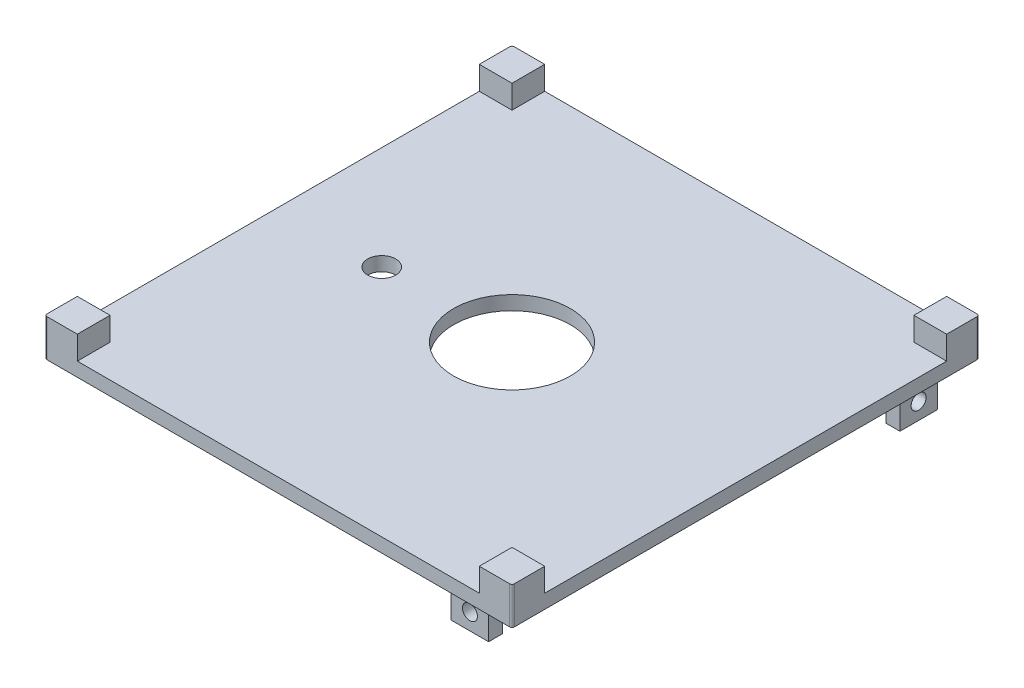
SolidWorks part; units mm, degrees
material "6061-T6 (SS)"
ref_plane "Front Plane" through (0, 0, 0) normal (0, 0, 1) x (1, 0, 0)
ref_plane "Top Plane" through (0, 0, 0) normal (0, 1, 0) x (1, 0, 0)
ref_plane "Right Plane" through (0, 0, 0) normal (1, 0, 0) x (0, 0, -1)
sketch "Sketch1" plane through (0, 0, 0) normal (0, 1, 0) x (1, 0, 0)
  line L0 (50, -50) -> (-50, -50) construction
  line L1 (50, -50) -> (50, 50) construction
  line L2 (50, 50) -> (-50, 50) construction
  line L3 (-50, -50) -> (-50, 50) construction
  line L4 (50, -50) -> (-50, 50) construction
  line L5 (50, 50) -> (-50, -50) construction
  line L6 (-50, 50) -> (-43, 50) construction
  line L7 (-50, 50) -> (-50, 43) construction
  line L8 (-50, 43) -> (-43, 43) construction
  line L9 (-43, 50) -> (-43, 43) construction
  line L10 (-50, -50) -> (-43, -50) construction
  line L11 (-50, -50) -> (-50, -43) construction
  line L12 (-50, -43) -> (-43, -43) construction
  line L13 (-43, -50) -> (-43, -43) construction
  line L14 (50, -50) -> (43, -50) construction
  line L15 (50, -50) -> (50, -43) construction
  line L16 (50, -43) -> (43, -43) construction
  line L17 (43, -50) -> (43, -43) construction
  line L18 (50, 50) -> (43, 50) construction
  line L19 (50, 50) -> (50, 43) construction
  line L20 (50, 43) -> (43, 43) construction
  line L21 (43, 50) -> (43, 43) construction
  line L22 (-32.625, 45.061) -> (33.923, 45.061) construction
  line L23 (-32.625, 45.061) -> (-32.625, 35.082) construction
  line L24 (-32.625, 35.082) -> (33.923, 35.082) construction
  line L25 (33.923, 45.061) -> (33.923, 35.082) construction
  line L26 (-50, 50) -> (-35, 50)
  line L27 (-50, 50) -> (-50, 48)
  line L28 (-50, 48) -> (-35, 48)
  line L29 (-35, 50) -> (-35, 48)
  line L30 (-50, 50) -> (-48, 50)
  line L31 (-50, 50) -> (-50, 35)
  line L32 (-50, 35) -> (-48, 35)
  line L33 (-48, 50) -> (-48, 35)
  line L34 (50, 50) -> (35, 50)
  line L35 (50, 50) -> (50, 48)
  line L36 (50, 48) -> (35, 48)
  line L37 (35, 50) -> (35, 48)
  line L38 (50, 50) -> (48, 50)
  line L39 (50, 50) -> (50, 35)
  line L40 (50, 35) -> (48, 35)
  line L41 (48, 50) -> (48, 35)
  line L42 (50, -50) -> (48, -50)
  line L43 (50, -50) -> (50, -35)
  line L44 (50, -35) -> (48, -35)
  line L45 (48, -50) -> (48, -35)
  line L46 (50, -50) -> (35, -50)
  line L47 (50, -50) -> (50, -48)
  line L48 (50, -48) -> (35, -48)
  line L49 (35, -50) -> (35, -48)
  line L50 (-50, -50) -> (-35, -50)
  line L51 (-50, -50) -> (-50, -48)
  line L52 (-50, -48) -> (-35, -48)
  line L53 (-35, -50) -> (-35, -48)
  line L54 (-50, -50) -> (-48, -50)
  line L55 (-50, -50) -> (-50, -35)
  line L56 (-50, -35) -> (-48, -35)
  line L57 (-48, -50) -> (-48, -35)
  circle A0 centre (-36.2, 42.85) radius 1.6
  circle A1 centre (37.5, 42.85) radius 1.6
  circle A2 centre (40, -42.85) radius 1.6
  circle A3 centre (-40, -42.85) radius 1.6
  point P0 (0, 0)
  point P5 (0, 0)
  point P6 (0, 0)
  dimension "D6" = 3.2
  dimension "D1" = 100
  dimension "D2" = 7
  dimension "D3" = 7
  dimension "D4" = 7
  dimension "D5" = 7
  dimension "D7" = 7.15
  dimension "D8" = 13.8
  dimension "D9" = 10
  dimension "D10" = 7.15
  dimension "D11" = 10
  dimension "D12" = 7.15
  dimension "D13" = 17.375
  dimension "D14" = 4.939
  dimension "D15" = 14.918
  dimension "D16" = 16.077
  dimension "D17" = 73.7
  dimension "D18" = 15
  dimension "D19" = 2
  dimension "D20" = 15
  dimension "D21" = 2
  dimension "D22" = 2
  dimension "D23" = 15
  dimension "D24" = 15
  dimension "D25" = 2
  dimension "D26" = 15
  dimension "D27" = 2
  dimension "D28" = 2
  dimension "D29" = 15
  dimension "D30" = 15
  dimension "D31" = 15
  dimension "D32" = 2
  dimension "D33" = 2
  dimension "D34" = 100
sketch "Sketch2" plane through (0, 0, 0) normal (0, 1, 0) x (1, 0, 0)
  line L0 (50, -50) -> (50, 50) construction
  line L1 (50, -50) -> (-50, -50) construction
  line L2 (-50, -50) -> (-50, 50) construction
  line L3 (50, 50) -> (-50, 50) construction
  line L4 (50, -50) -> (50, 50)
  line L5 (50, -50) -> (-50, -50)
  line L6 (-50, -50) -> (-50, 50)
  line L7 (50, 50) -> (-50, 50)
  circle A0 centre (0, 0) radius 12.5
  dimension "D1" = 25
extrude "Boss-Extrude1" add sketch "Sketch2" along normal blind 3
sketch "Sketch3" plane through (0, 3, 0) normal (0, 1, 0) x (1, 0, 0)
  line L0 (-50, 43) -> (-43, 43) construction
  line L1 (-50, 50) -> (-50, 43) construction
  line L2 (-43, 50) -> (-43, 43) construction
  line L3 (-50, 50) -> (-43, 50) construction
  line L4 (-50, 43) -> (-43, 43)
  line L5 (-50, 50) -> (-50, 43)
  line L6 (-43, 50) -> (-43, 43)
  line L7 (-50, 50) -> (-43, 50)
  line L8 (50, 43) -> (43, 43) construction
  line L9 (50, 50) -> (50, 43) construction
  line L10 (43, 50) -> (43, 43) construction
  line L11 (50, 50) -> (43, 50) construction
  line L12 (50, -43) -> (43, -43) construction
  line L13 (50, -50) -> (50, -43) construction
  line L14 (43, -50) -> (43, -43) construction
  line L15 (50, -50) -> (43, -50) construction
  line L16 (-50, -43) -> (-43, -43) construction
  line L17 (-50, -50) -> (-50, -43) construction
  line L18 (-43, -50) -> (-43, -43) construction
  line L19 (-50, -50) -> (-43, -50) construction
  line L20 (50, 43) -> (43, 43)
  line L21 (50, 50) -> (50, 43)
  line L22 (43, 50) -> (43, 43)
  line L23 (50, 50) -> (43, 50)
  line L24 (50, -43) -> (43, -43)
  line L25 (50, -50) -> (50, -43)
  line L26 (43, -50) -> (43, -43)
  line L27 (50, -50) -> (43, -50)
  line L28 (-50, -43) -> (-43, -43)
  line L29 (-50, -50) -> (-50, -43)
  line L30 (-43, -50) -> (-43, -43)
  line L31 (-50, -50) -> (-43, -50)
extrude "Boss-Extrude2" add sketch "Sketch3" along normal blind 5
sketch "Sketch4" plane through (0, 0, 0) normal (0, -1, 0) x (1, 0, 0)
  line L11 (50, -43) -> (43, -43) construction
  line L12 (48, -35) -> (45, -35)
  line L13 (48, -35) -> (48, -43)
  line L14 (48, -43) -> (45, -43)
  line L15 (45, -35) -> (45, -43)
  line L17 (35, 48) -> (43, 48)
  line L18 (35, 48) -> (35, 45)
  line L19 (35, 45) -> (43, 45)
  line L20 (43, 48) -> (43, 45)
  line L26 (-50, 43) -> (-43, 43) construction
  line L27 (-48, 35) -> (-45, 35)
  line L28 (-48, 35) -> (-48, 43)
  line L29 (-48, 43) -> (-45, 43)
  line L30 (-45, 35) -> (-45, 43)
  line L36 (43, 50) -> (43, 43) construction
  line L40 (-50, -48) -> (-35, -48) construction
  line L41 (-43, -48) -> (-35, -48)
  line L42 (-43, -48) -> (-43, -45)
  line L43 (-43, -45) -> (-35, -45)
  line L44 (-35, -48) -> (-35, -45)
  line L45 (-43, -50) -> (-43, -43) construction
  dimension "D1" = 3
extrude "Boss-Extrude3" add sketch "Sketch4" along normal blind 7
sketch "Sketch5" plane through (0, 0, -48) normal (0, 0, -1) x (-1, 0, 0)
  line L2 (43, -7) -> (35, -7) construction
  line L3 (43, -7) -> (43, 0) construction
  line L4 (-35, -7) -> (-43, -7) construction
  circle A1 centre (39, -3.5) radius 1.6
  circle A2 centre (-39, -3.5) radius 1.6
  point P5 (43, -3.5)
  point P12 (39, -7)
  point P15 (-39, -7)
  dimension "D2" = 3.2
extrude "Cut-Extrude1" cut sketch "Sketch5" against normal through all
sketch "Sketch6" plane through (0, 8, 0) normal (0, 1, 0) x (1, 0, 0)
  line L0 (-50, 43) -> (-43, 43) construction
  line L1 (-43, 43) -> (-43, 50) construction
  line L2 (43, 43) -> (50, 43) construction
  line L3 (-43, -50) -> (-43, -43) construction
  circle A0 centre (-46.5, 46.5) radius 1.5
  circle A1 centre (46.5, 46.5) radius 1.5
  circle A2 centre (46.5, -46.5) radius 1.5
  circle A3 centre (-46.5, -46.5) radius 1.5
  point P11 (-46.5, 43)
  point P14 (-43, 46.5)
  point P18 (46.5, 43)
  point P25 (-43, -46.5)
  dimension "D1" = 3
extrude "Cut-Extrude2" [suppressed] cut sketch "Sketch6" against normal through all
sketch "Sketch7" [suppressed] plane through (0, 0, 0) normal (0, -1, 0) x (1, 0, 0)
  circle A0 centre (46.5, 46.5) radius 1.5 construction
  circle A1 centre (-46.5, 46.5) radius 1.5 construction
  circle A2 centre (-46.5, -46.5) radius 1.5 construction
  circle A3 centre (46.5, -46.5) radius 1.5 construction
  circle A4 centre (46.5, 46.5) radius 1.5
  circle A5 centre (-46.5, 46.5) radius 1.5
  circle A6 centre (-46.5, -46.5) radius 1.5
  circle A7 centre (46.5, -46.5) radius 1.5
  circle A8 centre (46.5, -46.5) radius 2.5
  circle A9 centre (-46.5, -46.5) radius 2.5
  circle A10 centre (-46.5, 46.5) radius 2.5
  circle A11 centre (46.5, 46.5) radius 2.5
  dimension "D1" = 1
extrude "Cut-Extrude3" [suppressed] cut sketch "Sketch7" against normal blind 5
sketch "Sketch8" plane through (48, 0, 0) normal (1, 0, 0) x (0, 0, -1)
  line L0 (-43, -7) -> (-43, 0) construction
  line L1 (43, -7) -> (35, -7) construction
  line L2 (-35, -7) -> (-43, -7) construction
  circle A0 centre (-39, -3.5) radius 1.6
  circle A1 centre (39, -3.5) radius 1.6
  point P6 (-43, -3.5)
  point P9 (39, -7)
  point P12 (-39, -7)
  dimension "D1" = 3.2
extrude "Cut-Extrude4" cut sketch "Sketch8" against normal through all
sketch "Sketch9" plane through (0, 3, 0) normal (0, 1, 0) x (1, 0, 0)
  line L1 (-50, 43) -> (-50, -43) construction
  circle A1 centre (-27.8766, 0) radius 3
  point P4 (-50, 0)
  dimension "D1" = 6
extrude "Cut-Extrude5" cut sketch "Sketch9" against normal blind 10
fillet "Fillet1" radius 0.5 4 edges at (-50, 4, 50) (50, 4, 50) (50, 4, -50) (-50, 4, -50)
